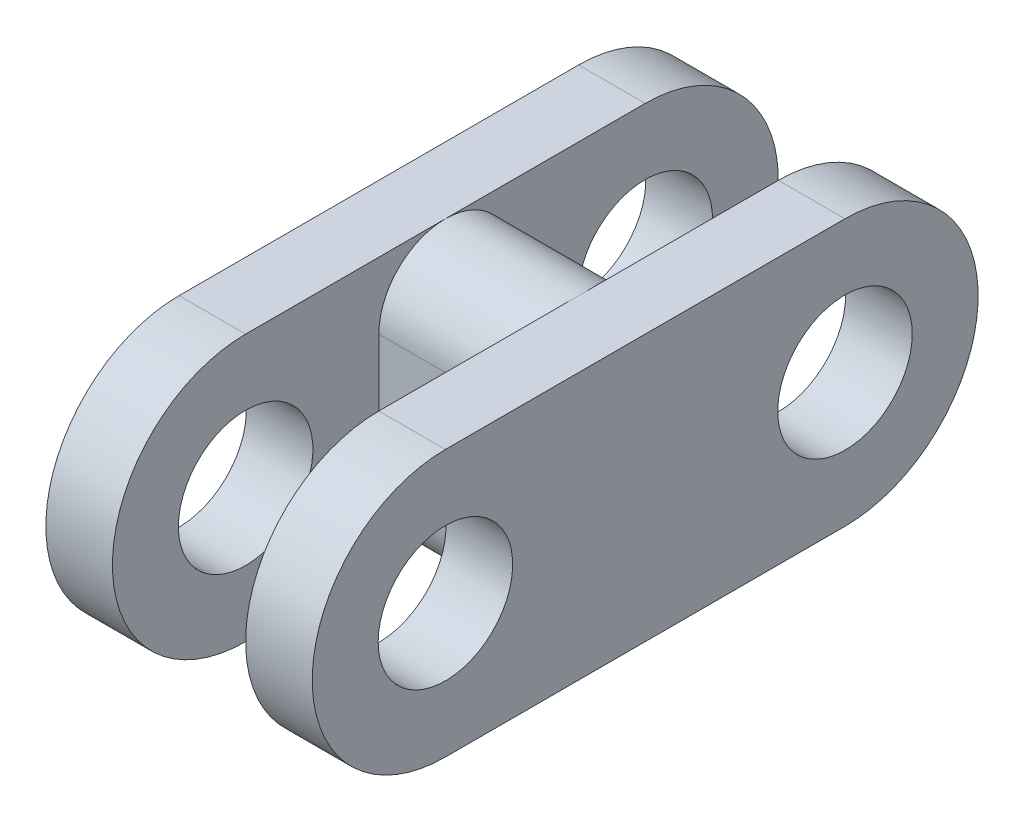
SolidWorks part; units mm, degrees
ref_plane "Front Plane" through (0, 0, 0) normal (0, 0, 1) x (1, 0, 0)
ref_plane "Top Plane" through (0, 0, 0) normal (0, 1, 0) x (1, 0, 0)
ref_plane "Right Plane" through (0, 0, 0) normal (1, 0, 0) x (0, 0, -1)
ref_plane "Plane1" through (0, 0, 0) normal (-1, 0, 0) x (0, -1, 0)
sketch "Sketch1" plane through (0, 0, 0) normal (-1, 0, 0) x (0, -1, 0)
  line L0 (0, 20) -> (0, 5)
  line L1 (10, 5) -> (10, 20)
  arc A0 (0, 5) -> (10, 5) centre (5, 5) ccw
  arc A1 (10, 20) -> (0, 20) centre (5, 20) ccw
extrude "Boss-Extrude1" add sketch "Sketch1" against normal blind 2.5
sketch "Sketch2" plane through (2.5, 0, 0) normal (1, 0, 0) x (0, 0, -1)
  line L0 (-15, -7.5) -> (-15, -2.5)
  line L1 (-10, -2.5) -> (-10, -7.5)
  arc A0 (-15, -2.5) -> (-10, -2.5) centre (-12.5, -2.5) cw
  arc A1 (-10, -7.5) -> (-15, -7.5) centre (-12.5, -7.5) cw
extrude "Boss-Extrude2" add sketch "Sketch2" along normal blind 5
sketch "Sketch3" plane through (7.5, 0, 0) normal (1, 0, 0) x (0, 0, -1)
  line L0 (-20, 0) -> (-5, 0)
  line L1 (-5, -10) -> (-20, -10)
  arc A0 (-5, 0) -> (-5, -10) centre (-5, -5) cw
  arc A1 (-20, -10) -> (-20, 0) centre (-20, -5) cw
extrude "Boss-Extrude3" add sketch "Sketch3" along normal blind 2.5
hole_wizard "Hole1" positions "Sketch5" profile "Sketch4" legacy
sketch "Sketch5" plane through (10, 0, 0) normal (1, 0, 0) x (0, 0, -1)
  point P0 (-5, -5)
sketch "Sketch4" plane through (10, -5, 5) normal (0, 1, 0) x (0, 0, -1)
  line L0 (0, 0) -> (0, 2.5)
  line L1 (0, 2.5) -> (2.525, 2.5)
  line L2 (2.525, 2.5) -> (2.525, 0)
  line L3 (2.525, 0) -> (0, 0)
  line L4 (0, 110) -> (0, -10) construction
  dimension "Diameter" = 5.05
  dimension "Depth" = 2.5
hole_wizard "Hole2" positions "Sketch7" profile "Sketch6" legacy
sketch "Sketch7" plane through (7.5, 0, 0) normal (-1, 0, 0) x (0, 0, 1)
  point P0 (20, -5)
sketch "Sketch6" plane through (7.5, -5, 20) normal (0, 1, 0) x (0, 0, 1)
  line L0 (0, 0) -> (0, 2.5)
  line L1 (0, 2.5) -> (2.525, 2.5)
  line L2 (2.525, 2.5) -> (2.525, 0)
  line L3 (2.525, 0) -> (0, 0)
  line L4 (0, 110) -> (0, -10) construction
  dimension "Diameter" = 5.05
  dimension "Depth" = 2.5
hole_wizard "Hole3" positions "Sketch9" profile "Sketch8" legacy
sketch "Sketch9" plane through (0, 0, 0) normal (-1, 0, 0) x (0, 0, 1)
  point P0 (20, -5)
  point P1 (5, -5)
sketch "Sketch8" plane through (0, -5, 20) normal (0, 1, 0) x (0, 0, 1)
  line L0 (0, 0) -> (0, 10)
  line L1 (0, 10) -> (2.525, 10)
  line L2 (2.525, 10) -> (2.525, 0)
  line L3 (2.525, 0) -> (0, 0)
  line L4 (0, 110) -> (0, -10) construction
  dimension "Diameter" = 5.05
  dimension "Depth" = 10
